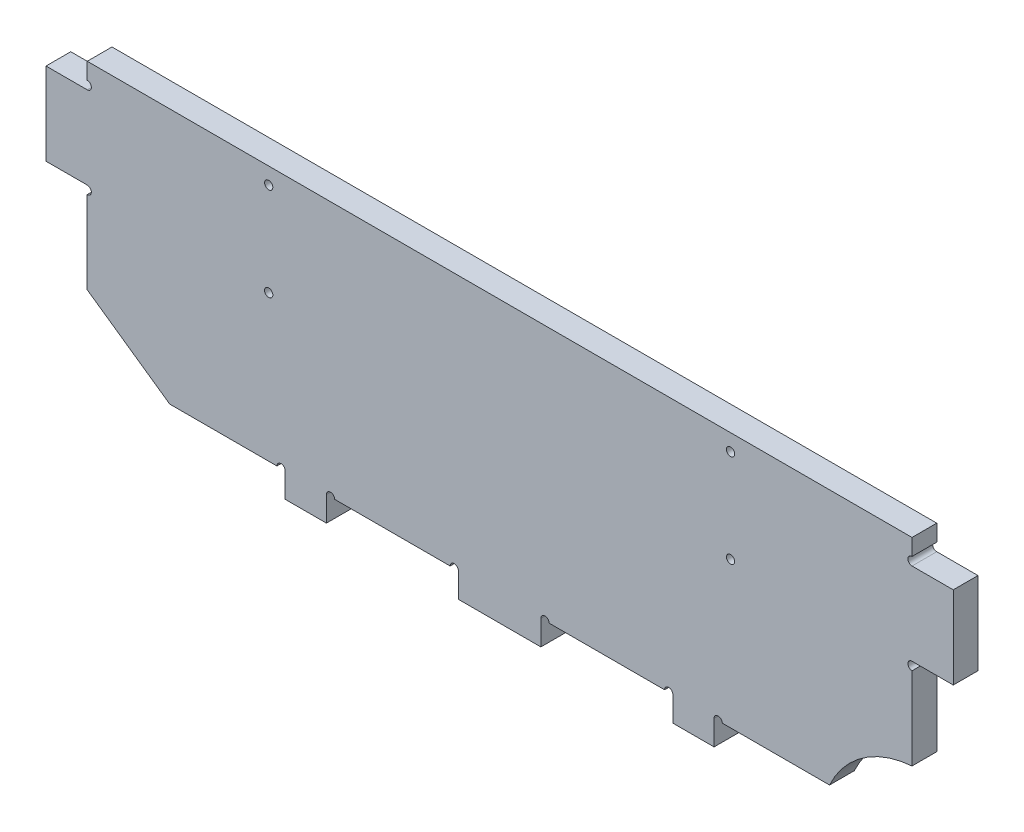
SolidWorks part; units mm, degrees
ref_plane "Front Plane" through (0, 0, 0) normal (0, 0, 1) x (1, 0, 0)
ref_plane "Top Plane" through (0, 0, 0) normal (0, 1, 0) x (1, 0, 0)
ref_plane "Right Plane" through (0, 0, 0) normal (1, 0, 0) x (0, 0, -1)
sketch "Sketch1" plane through (0, 0, 0) normal (0, 0, 1) x (1, 0, 0)
  line L0 (-5, 0) -> (5, 0)
  line L1 (5, 0) -> (5, 3)
  line L2 (5, 3) -> (21, 3)
  line L3 (21, 3) -> (21, 0)
  line L4 (21, 0) -> (26, 0)
  line L5 (26, 0) -> (26, 3)
  line L6 (26, 3) -> (40, 3)
  line L8 (50, 10) -> (50, 21)
  line L9 (50, 21) -> (55, 21)
  line L10 (55, 21) -> (55, 31)
  line L11 (55, 31) -> (50, 31)
  line L12 (50, 34) -> (0, 34)
  line L13 (0, 34) -> (0, 0) construction
  line L14 (-50, 34) -> (0, 34)
  line L15 (-5, 0) -> (-5, 3)
  line L16 (-5, 3) -> (-21, 3)
  line L17 (-21, 3) -> (-21, 0)
  line L18 (-21, 0) -> (-26, 0)
  line L19 (-26, 0) -> (-26, 3)
  line L20 (-26, 3) -> (-40, 3)
  line L21 (-40, 3) -> (-50, 10)
  line L22 (-50, 10) -> (-50, 21)
  line L23 (-50, 21) -> (-55, 21)
  line L24 (-55, 21) -> (-55, 31)
  line L25 (-50, 31) -> (-50, 34)
  line L26 (50, 31) -> (50, 34)
  line L27 (-55, 31) -> (-50, 31)
  circle A0 centre (28, 32) radius 0.5
  circle A1 centre (28, 20.7) radius 0.5
  circle A2 centre (-28, 20.7) radius 0.5
  circle A3 centre (-28, 32) radius 0.5
  arc A4 (40, 3) -> (50, 10) centre (50.925, -1.9643) cw
  dimension "D13" = 1
  dimension "D15" = 2
  dimension "D17" = 12
  dimension "D1" = 5
  dimension "D2" = 5
  dimension "D3" = 3
  dimension "D4" = 16
  dimension "D5" = 55
  dimension "D6" = 5
  dimension "D7" = 5
  dimension "D8" = 10
  dimension "D9" = 31
  dimension "D10" = 3
  dimension "D11" = 10
  dimension "D12" = 7
  dimension "D14" = 11.3
  dimension "D16" = 22
extrude "Boss-Extrude1" add sketch "Sketch1" along normal blind 3
sketch "Sketch3" plane through (0, 0, 3) normal (0, 0, 1) x (1, 0, 0)
  line L0 (5, 3) -> (21, 3) construction
  line L1 (26, 3) -> (40, 3) construction
  line L2 (50, 10) -> (50, 21) construction
  line L5 (0, 34) -> (0, 0) construction
  arc A0 (5, 3) -> (6, 3) centre (5.5, 3) cw
  arc A1 (21, 3) -> (20, 3) centre (20.5, 3) ccw
  arc A2 (26, 3) -> (27, 3) centre (26.5, 3) cw
  arc A3 (50, 21) -> (50, 20) centre (50, 20.5) ccw
  arc A4 (50, 31) -> (50, 32) centre (50, 31.5) cw
  arc A5 (-50, 31) -> (-50, 32) centre (-50, 31.5) ccw
  arc A6 (-50, 21) -> (-50, 20) centre (-50, 20.5) cw
  arc A7 (-26, 3) -> (-27, 3) centre (-26.5, 3) ccw
  arc A8 (-21, 3) -> (-20, 3) centre (-20.5, 3) cw
  arc A9 (-5, 3) -> (-6, 3) centre (-5.5, 3) ccw
  line M4 (5, 3) -> (21, 3)
  line M8 (26, 3) -> (40, 3)
  line M10 (50, 10) -> (50, 21)
  line M14 (50, 31) -> (50, 34)
  line M16 (-50, 34) -> (-50, 31)
  line M20 (-50, 21) -> (-50, 10)
  line M22 (-40, 3) -> (-26, 3)
  line M26 (-21, 3) -> (-5, 3)
  dimension "D1" = 0.5
extrude "Cut-Extrude2" cut sketch "Sketch3" against normal through all contours A5 M16 | A6 M20 | A7 M22 | A8 M26 | A9 M26 | A0 M4 | A1 M4 | A2 M8 | A3 M10 | A4 M14
